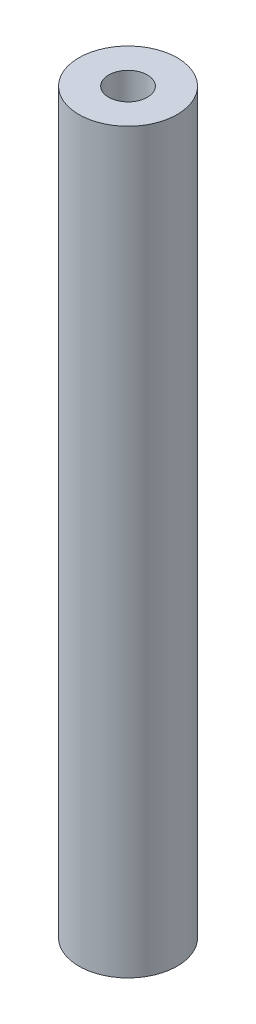
SolidWorks part; units mm, degrees
ref_plane "Front Plane" through (0, 0, 0) normal (0, 0, 1) x (1, 0, 0)
ref_plane "Top Plane" through (0, 0, 0) normal (0, 1, 0) x (1, 0, 0)
ref_plane "Right Plane" through (0, 0, 0) normal (1, 0, 0) x (0, 0, -1)
sketch "Sketch1" plane through (0, 0, 0) normal (0, 1, 0) x (1, 0, 0)
  circle A0 centre (0, 0) radius 1
  circle A1 centre (0, 0) radius 2.54
  dimension "D1" = 2
  dimension "D2" = 5.08
extrude "Boss-Extrude1" add sketch "Sketch1" along normal blind 38.1
